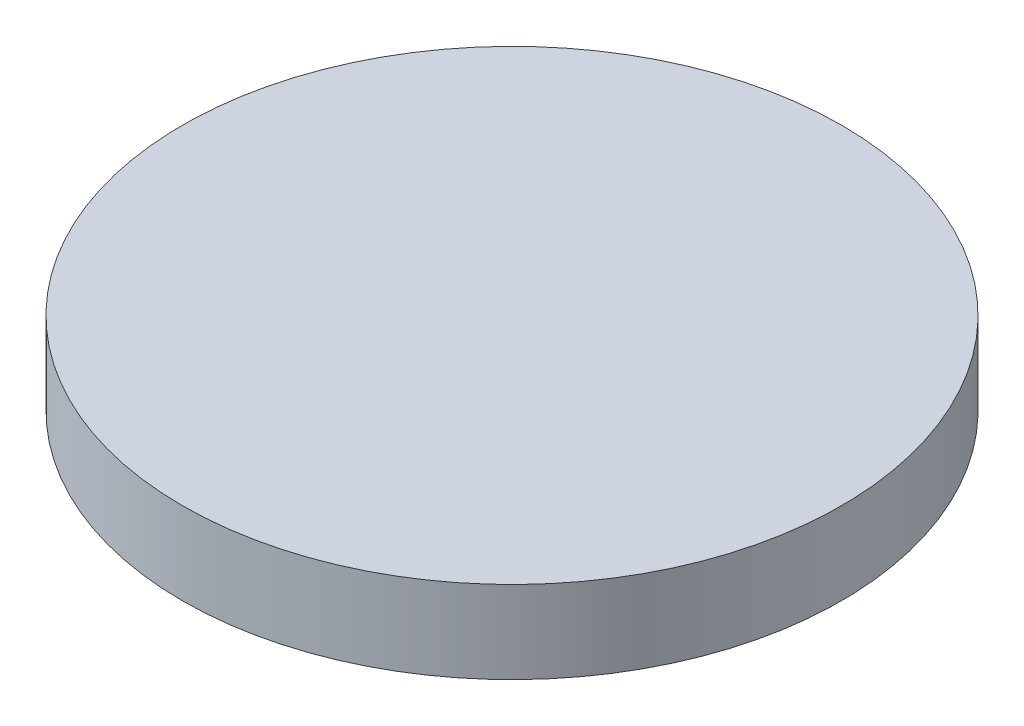
SolidWorks part; units mm, degrees
ref_plane "前视基准面" through (0, 0, 0) normal (0, 0, 1) x (1, 0, 0)
ref_plane "上视基准面" through (0, 0, 0) normal (0, 1, 0) x (1, 0, 0)
ref_plane "右视基准面" through (0, 0, 0) normal (1, 0, 0) x (0, 0, -1)
sketch "草图1" plane through (0, 0, 0) normal (0, 1, 0) x (1, 0, 0)
  circle A0 centre (0, 0) radius 10
extrude "凸台-拉伸1" add sketch "草图1" along normal blind 2.5
